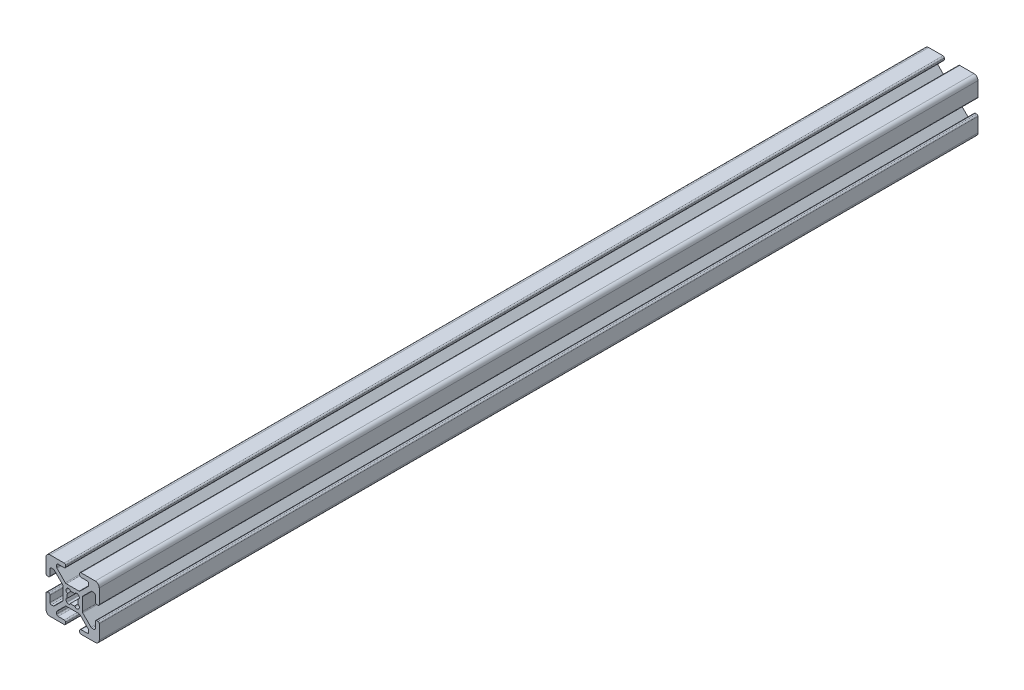
SolidWorks part; units mm, degrees
ref_plane "Front Plane" through (0, 0, 0) normal (0, 0, 1) x (1, 0, 0)
ref_plane "Top Plane" through (0, 0, 0) normal (0, 1, 0) x (1, 0, 0)
ref_plane "Right Plane" through (0, 0, 0) normal (1, 0, 0) x (0, 0, -1)
sketch "Sketch1" plane through (0, 0, 0) normal (0, 0, 1) x (1, 0, 0)
  line L0 (-5.0323, -0.3411) -> (-5.5163, -0.3411)
  line L1 (-6.0243, 0.1669) -> (-6.0243, 2.5159)
  line L2 (-4.5243, 0.1669) -> (-4.5243, 5.5289)
  line L3 (-10.8693, -5.355) -> (-10.8693, -0.5871)
  line L4 (-7.2582, 3.0239) -> (-6.5323, 3.0239)
  line L5 (-7.6174, 2.8752) -> (-10.7205, -0.2279)
  line L6 (-5.0323, -5.6011) -> (-5.5163, -5.6011)
  line L7 (-4.5243, -6.1091) -> (-4.5243, -11.4711)
  line L8 (-6.0243, -6.1091) -> (-6.0243, -8.4581)
  line L9 (-7.2582, -8.9661) -> (-6.5323, -8.9661)
  line L10 (-7.6174, -8.8173) -> (-10.7205, -5.7142)
  line L11 (-12.3994, -5.2756) -> (-12.2198, -5.096)
  line L12 (-17.1543, 6.5209) -> (-17.1543, 6.0369)
  line L13 (-17.6623, 7.0289) -> (-23.0243, 7.0289)
  line L14 (-17.6623, 5.5289) -> (-20.0113, 5.5289)
  line L15 (-12.1404, 0.6839) -> (-16.9082, 0.6839)
  line L16 (-20.5193, 4.295) -> (-20.5193, 5.0209)
  line L17 (-20.3705, 3.9358) -> (-17.2674, 0.8327)
  line L18 (-11.8943, 6.5209) -> (-11.8943, 6.0369)
  line L19 (-11.3863, 7.0289) -> (-6.0243, 7.0289)
  line L20 (-11.3863, 5.5289) -> (-9.0373, 5.5289)
  line L21 (-8.5293, 4.295) -> (-8.5293, 5.0209)
  line L22 (-8.6781, 3.9358) -> (-11.7812, 0.8327)
  line L23 (-12.2198, -0.8462) -> (-12.3994, -0.6666)
  line L24 (-24.0163, -5.6011) -> (-23.5323, -5.6011)
  line L25 (-24.5243, -6.1091) -> (-24.5243, -11.4711)
  line L26 (-23.0243, -6.1091) -> (-23.0243, -8.4581)
  line L27 (-18.1793, -0.5871) -> (-18.1793, -5.355)
  line L28 (-21.7904, -8.9661) -> (-22.5163, -8.9661)
  line L29 (-21.4312, -8.8173) -> (-18.3281, -5.7142)
  line L30 (-24.0163, -0.3411) -> (-23.5323, -0.3411)
  line L31 (-24.5243, 0.1669) -> (-24.5243, 5.5289)
  line L32 (-23.0243, 0.1669) -> (-23.0243, 2.5159)
  line L33 (-21.7904, 3.0239) -> (-22.5163, 3.0239)
  line L34 (-21.4312, 2.8752) -> (-18.3281, -0.2279)
  line L35 (-16.6492, -0.6666) -> (-16.8288, -0.8462)
  line L36 (-11.8943, -12.4631) -> (-11.8943, -11.9791)
  line L37 (-11.3863, -12.9711) -> (-6.0243, -12.9711)
  line L38 (-11.3863, -11.4711) -> (-9.0373, -11.4711)
  line L39 (-16.9082, -6.6261) -> (-12.1404, -6.6261)
  line L40 (-8.5293, -10.2371) -> (-8.5293, -10.9631)
  line L41 (-8.6781, -9.8779) -> (-11.7812, -6.7748)
  line L42 (-17.1543, -12.4631) -> (-17.1543, -11.9791)
  line L43 (-17.6623, -12.9711) -> (-23.0243, -12.9711)
  line L44 (-17.6623, -11.4711) -> (-20.0113, -11.4711)
  line L45 (-20.5193, -10.2371) -> (-20.5193, -10.9631)
  line L46 (-20.3705, -9.8779) -> (-17.2674, -6.7748)
  line L47 (-16.8288, -5.096) -> (-16.6492, -5.2756)
  arc A0 (-15.3283, -4.9062) -> (-13.7203, -4.9062) centre (-14.5243, -2.9711) ccw
  arc A1 (-6.0243, 2.5159) -> (-6.5323, 3.0239) centre (-6.5323, 2.5159) ccw
  arc A2 (-7.2582, 3.0239) -> (-7.6174, 2.8752) centre (-7.2582, 2.5159) ccw
  arc A3 (-10.7205, -0.2279) -> (-10.8693, -0.5871) centre (-10.3613, -0.5871) ccw
  arc A4 (-10.8693, -5.355) -> (-10.7205, -5.7142) centre (-10.3613, -5.355) ccw
  arc A5 (-7.6174, -8.8173) -> (-7.2582, -8.9661) centre (-7.2582, -8.4581) ccw
  arc A6 (-6.5323, -8.9661) -> (-6.0243, -8.4581) centre (-6.5323, -8.4581) ccw
  arc A7 (-5.5163, -5.6011) -> (-6.0243, -6.1091) centre (-5.5163, -6.1091) ccw
  arc A8 (-4.5243, -6.1091) -> (-5.0323, -5.6011) centre (-5.0323, -6.1091) ccw
  arc A9 (-5.0323, -0.3411) -> (-4.5243, 0.1669) centre (-5.0323, 0.1669) ccw
  arc A10 (-6.0243, 0.1669) -> (-5.5163, -0.3411) centre (-5.5163, 0.1669) ccw
  arc A11 (-13.7203, -4.9062) -> (-12.3994, -5.2756) centre (-12.9559, -4.7191) ccw
  arc A12 (-12.2198, -5.096) -> (-12.5892, -3.775) centre (-12.7763, -4.5395) ccw
  arc A13 (-17.1543, 6.5209) -> (-17.6623, 7.0289) centre (-17.6623, 6.5209) ccw
  arc A14 (-17.6623, 5.5289) -> (-17.1543, 6.0369) centre (-17.6623, 6.0369) ccw
  arc A15 (-12.5892, -3.775) -> (-12.5892, -2.1671) centre (-14.5243, -2.9711) ccw
  arc A16 (-17.2674, 0.8327) -> (-16.9082, 0.6839) centre (-16.9082, 1.1919) ccw
  arc A17 (-20.0113, 5.5289) -> (-20.5193, 5.0209) centre (-20.0113, 5.0209) ccw
  arc A18 (-20.5193, 4.295) -> (-20.3705, 3.9358) centre (-20.0113, 4.295) ccw
  arc A19 (-11.8943, 6.0369) -> (-11.3863, 5.5289) centre (-11.3863, 6.0369) ccw
  arc A20 (-11.3863, 7.0289) -> (-11.8943, 6.5209) centre (-11.3863, 6.5209) ccw
  arc A21 (-8.5293, 5.0209) -> (-9.0373, 5.5289) centre (-9.0373, 5.0209) ccw
  arc A22 (-8.6781, 3.9358) -> (-8.5293, 4.295) centre (-9.0373, 4.295) ccw
  arc A23 (-12.1404, 0.6839) -> (-11.7812, 0.8327) centre (-12.1404, 1.1919) ccw
  arc A24 (-12.5892, -2.1671) -> (-12.2198, -0.8462) centre (-12.7763, -1.4027) ccw
  arc A25 (-12.3994, -0.6666) -> (-13.7203, -1.0359) centre (-12.9559, -1.223) ccw
  arc A26 (-24.0163, -5.6011) -> (-24.5243, -6.1091) centre (-24.0163, -6.1091) ccw
  arc A27 (-23.0243, -6.1091) -> (-23.5323, -5.6011) centre (-23.5323, -6.1091) ccw
  arc A28 (-13.7203, -1.0359) -> (-15.3283, -1.0359) centre (-14.5243, -2.9711) ccw
  arc A29 (-18.3281, -5.7142) -> (-18.1793, -5.355) centre (-18.6873, -5.355) ccw
  arc A30 (-23.0243, -8.4581) -> (-22.5163, -8.9661) centre (-22.5163, -8.4581) ccw
  arc A31 (-21.7904, -8.9661) -> (-21.4312, -8.8173) centre (-21.7904, -8.4581) ccw
  arc A32 (-23.5323, -0.3411) -> (-23.0243, 0.1669) centre (-23.5323, 0.1669) ccw
  arc A33 (-24.5243, 0.1669) -> (-24.0163, -0.3411) centre (-24.0163, 0.1669) ccw
  arc A34 (-22.5163, 3.0239) -> (-23.0243, 2.5159) centre (-22.5163, 2.5159) ccw
  arc A35 (-21.4312, 2.8752) -> (-21.7904, 3.0239) centre (-21.7904, 2.5159) ccw
  arc A36 (-18.1793, -0.5871) -> (-18.3281, -0.2279) centre (-18.6873, -0.5871) ccw
  arc A37 (-15.3283, -1.0359) -> (-16.6492, -0.6666) centre (-16.0927, -1.223) ccw
  arc A38 (-16.8288, -0.8462) -> (-16.4594, -2.1671) centre (-16.2723, -1.4027) ccw
  arc A39 (-11.8943, -12.4631) -> (-11.3863, -12.9711) centre (-11.3863, -12.4631) ccw
  arc A40 (-11.3863, -11.4711) -> (-11.8943, -11.9791) centre (-11.3863, -11.9791) ccw
  arc A41 (-16.4594, -2.1671) -> (-16.4594, -3.775) centre (-14.5243, -2.9711) ccw
  arc A42 (-11.7812, -6.7748) -> (-12.1404, -6.6261) centre (-12.1404, -7.1341) ccw
  arc A43 (-9.0373, -11.4711) -> (-8.5293, -10.9631) centre (-9.0373, -10.9631) ccw
  arc A44 (-8.5293, -10.2371) -> (-8.6781, -9.8779) centre (-9.0373, -10.2371) ccw
  arc A45 (-17.1543, -11.9791) -> (-17.6623, -11.4711) centre (-17.6623, -11.9791) ccw
  arc A46 (-17.6623, -12.9711) -> (-17.1543, -12.4631) centre (-17.6623, -12.4631) ccw
  arc A47 (-20.5193, -10.9631) -> (-20.0113, -11.4711) centre (-20.0113, -10.9631) ccw
  arc A48 (-20.3705, -9.8779) -> (-20.5193, -10.2371) centre (-20.0113, -10.2371) ccw
  arc A49 (-16.9082, -6.6261) -> (-17.2674, -6.7748) centre (-16.9082, -7.1341) ccw
  arc A50 (-16.4594, -3.775) -> (-16.8288, -5.096) centre (-16.2723, -4.5395) ccw
  arc A51 (-16.6492, -5.2756) -> (-15.3283, -4.9062) centre (-16.0927, -4.7191) ccw
  arc A52 (-4.5243, 5.5289) -> (-6.0243, 7.0289) centre (-6.0243, 5.5289) ccw
  arc A53 (-6.0243, -12.9711) -> (-4.5243, -11.4711) centre (-6.0243, -11.4711) ccw
  arc A54 (-24.5243, -11.4711) -> (-23.0243, -12.9711) centre (-23.0243, -11.4711) ccw
  arc A55 (-23.0243, 7.0289) -> (-24.5243, 5.5289) centre (-23.0243, 5.5289) ccw
extrude "Extrude1" add sketch "Sketch1" along normal blind 280 and the other way blind 50
